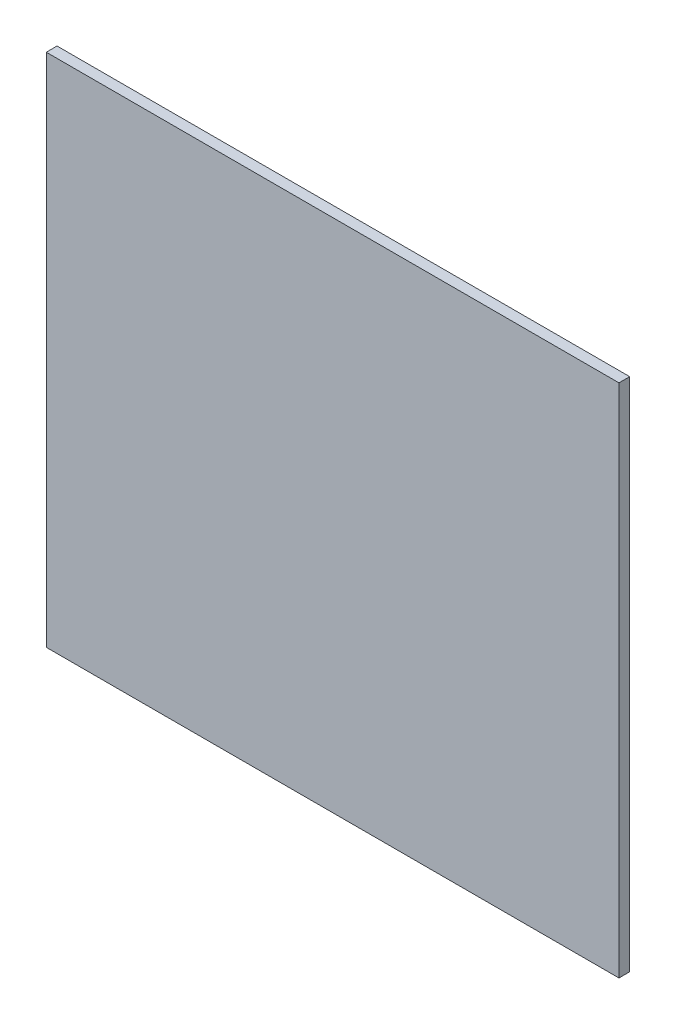
SolidWorks part; units mm, degrees
material "Oak"
ref_plane "Front" through (0, 0, 0) normal (0, 0, 1) x (1, 0, 0)
ref_plane "Top" through (0, 0, 0) normal (0, 1, 0) x (1, 0, 0)
ref_plane "Right" through (0, 0, 0) normal (1, 0, 0) x (0, 0, -1)
sketch "Sketch1" plane through (0, 0, -914.4) normal (0, 0, -1) x (-1, 0, 0)
  line L0 (0, 0) -> (-1016, 0)
  line L1 (-1016, 0) -> (-1016, 914.4)
  line L2 (-1016, 914.4) -> (0, 914.4)
  line L3 (0, 914.4) -> (0, 0)
  dimension "D1" = 914.4
extrude "Boss-Extrude1" add sketch "Sketch1" along normal blind 19.05
equation "\"D1@Sketch1\"=\"HEIGHT@shapeoko_enclosure.sldasm\" + \"MAT_THICKNESS@shapeoko_enclosure.sldasm\""
equation "\"D1@Boss-Extrude1\"=\"MAT_THICKNESS@shapeoko_enclosure.sldasm\""
